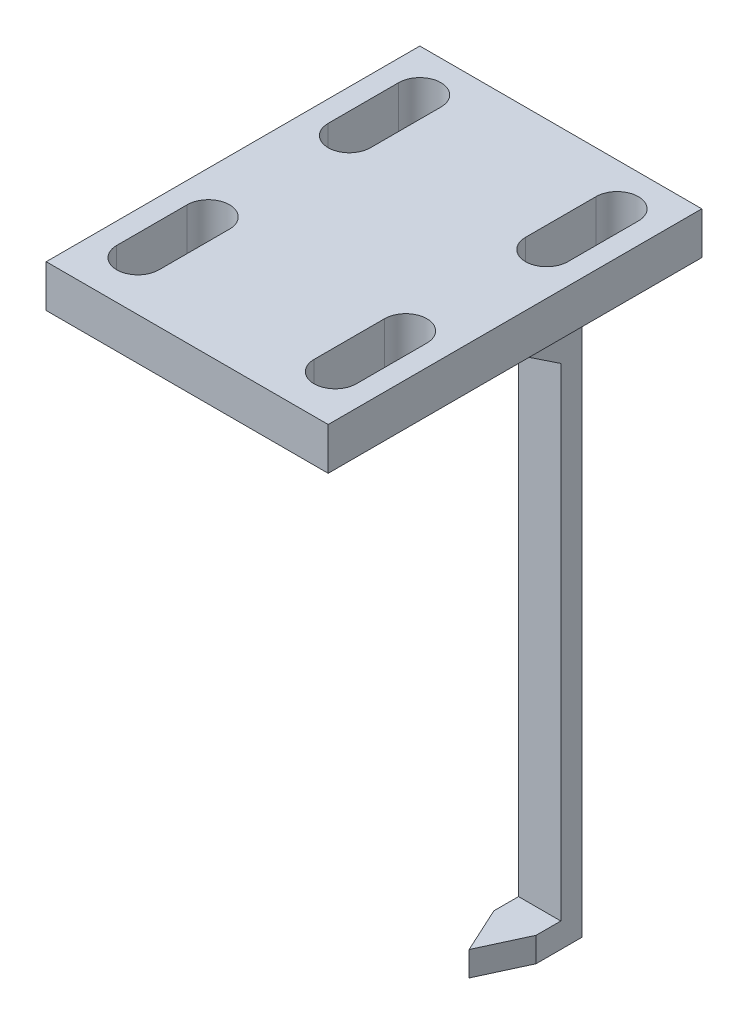
SolidWorks part; units mm, degrees
ref_plane "Спереди" through (0, 0, 0) normal (0, 0, 1) x (1, 0, 0)
ref_plane "Сверху" through (0, 0, 0) normal (0, 1, 0) x (1, 0, 0)
ref_plane "Справа" through (0, 0, 0) normal (1, 0, 0) x (0, 0, -1)
sketch "Sketch1" plane through (0, 0, 0) normal (0, 0, 1) x (1, 0, 0)
  line L0 (3, 46) -> (11.5, 46)
  line L1 (0, 0) -> (3, 0)
  line L2 (0, 0) -> (0, 46)
  line L4 (3, 0) -> (3, 46)
  line L5 (-8.5, 49) -> (11.5, 49)
  line L6 (-8.5, 49) -> (-8.5, 46)
  line L7 (-8.5, 46) -> (0, 46)
  line L8 (11.5, 49) -> (11.5, 46)
  dimension "D1" = 3
  dimension "D3" = 20
  dimension "D5" = 3
extrude "Boss-Extrude1" add sketch "Sketch1" along normal blind 1.5
sketch "Sketch2" plane through (0, 0, 1.5) normal (0, 0, 1) x (1, 0, 0)
  line L0 (3, 0) -> (3, 46) construction
  line L1 (0, 0) -> (3, 0)
  line L2 (0, 0) -> (0, 1.7509)
  line L3 (0, 1.7509) -> (3, 1.7509)
  line L4 (3, 0) -> (3, 1.7509)
extrude "Boss-Extrude2" add sketch "Sketch2" along normal blind 5
sketch "Sketch3" plane through (0, 0, 1.5) normal (0, 0, 1) x (1, 0, 0)
  line L2 (-8.5, 49) -> (11.5, 49)
  line L3 (-8.5, 49) -> (-8.5, 46)
  line L4 (-8.5, 46) -> (11.5, 46)
  line L5 (11.5, 49) -> (11.5, 46)
extrude "Boss-Extrude3" add sketch "Sketch3" along normal blind 25
sketch "Sketch4" plane through (0, 0, 0) normal (0, -1, 0) x (1, 0, 0)
  line L0 (1.5, 6.5) -> (0, 3.25)
  line L1 (0, 6.5) -> (3, 6.5) construction
  line L2 (0, 6.5) -> (0, 0) construction
  line L3 (0, 3.25) -> (-2.7211, 3.25)
  line L4 (-2.7211, 3.25) -> (-2.7211, 9.4475)
  line L5 (-2.7211, 9.4475) -> (6.0033, 9.4475)
  line L6 (6.0033, 9.4475) -> (5.6543, 3.25)
  line L7 (5.6543, 3.25) -> (3, 3.25)
  line L8 (3, 6.5) -> (3, 0) construction
  line L9 (3, 3.25) -> (1.5, 6.5)
extrude "Cut-Extrude1" cut sketch "Sketch4" against normal blind 5
sketch "Sketch5" plane through (0, 46, 0) normal (0, -1, 0) x (1, 0, 0)
  line L0 (-4, 8) -> (-4, 3)
  line L1 (-7, 8) -> (-7, 3)
  line L2 (10, 8) -> (10, 3)
  line L3 (7, 8) -> (7, 3)
  line L4 (10, 23) -> (10, 18)
  line L5 (7, 23) -> (7, 18)
  line L6 (-4, 23) -> (-4, 18)
  line L7 (-7, 23) -> (-7, 18)
  arc A0 (-7, 3) -> (-4, 3) centre (-5.5, 3) ccw
  arc A1 (7, 3) -> (10, 3) centre (8.5, 3) ccw
  arc A2 (10, 8) -> (7, 8) centre (8.5, 8) ccw
  arc A3 (7, 18) -> (10, 18) centre (8.5, 18) ccw
  arc A4 (-4, 8) -> (-7, 8) centre (-5.5, 8) ccw
  arc A5 (10, 23) -> (7, 23) centre (8.5, 23) ccw
  arc A6 (-7, 18) -> (-4, 18) centre (-5.5, 18) ccw
  arc A7 (-4, 23) -> (-7, 23) centre (-5.5, 23) ccw
  dimension "D1" = 3
  dimension "D6" = 3
  dimension "D2" = 2
  dimension "D3" = 3
  dimension "D7" = 5
  dimension "D4" = 2
extrude "Cut-Extrude2" cut sketch "Sketch5" against normal blind 10
sketch "Sketch6" plane through (0, 0, 0) normal (-1, 0, 0) x (0, 0, 1)
  line L0 (1.5, 46) -> (16.5, 46)
  line L1 (26.5, 46) -> (0, 46) construction
  line L2 (1.5, 46) -> (1.5, 36)
  line L3 (1.5, 46) -> (1.5, 1.7509) construction
  line L4 (1.5, 36) -> (16.5, 46)
  dimension "D1" = 10
  dimension "D2" = 15
extrude "Boss-Extrude4" add sketch "Sketch6" against normal blind 3
